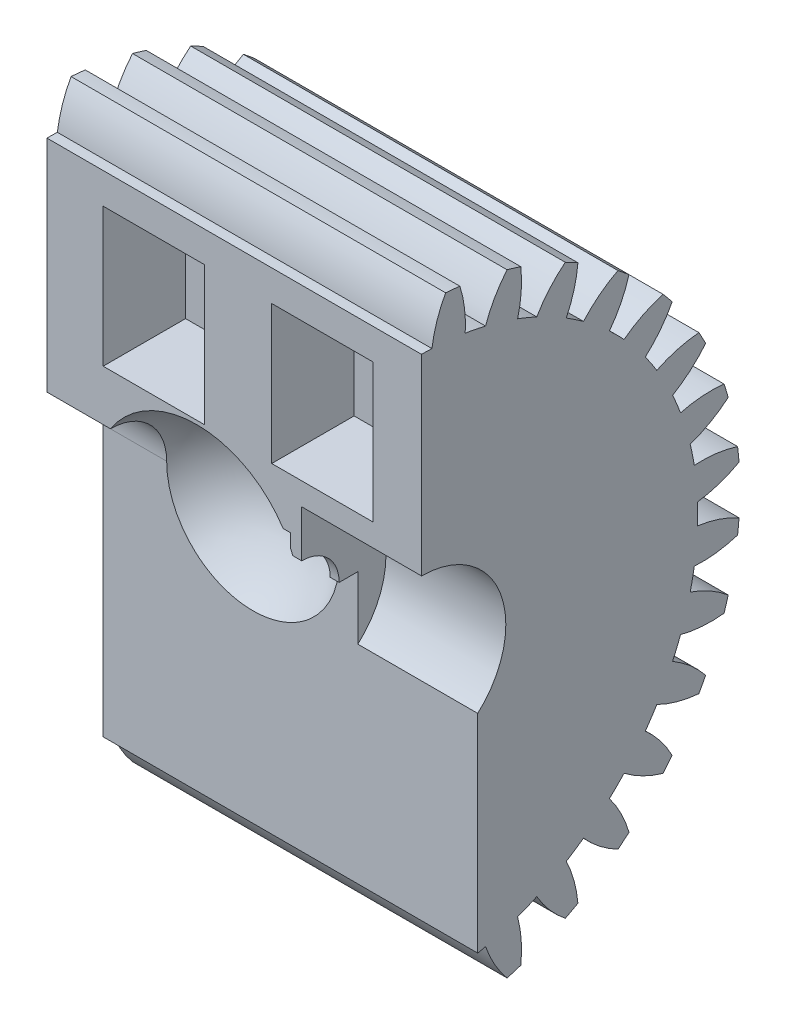
SolidWorks part; units mm, degrees
ref_plane "Plane1" through (0, 0, 0) normal (0, 0, 1) x (1, 0, 0)
ref_plane "Plane2" through (0, 0, 0) normal (0, 1, 0) x (1, 0, 0)
ref_plane "Plane3" through (0, 0, 0) normal (1, 0, 0) x (0, 0, -1)
other "Configuration Table"
sketch "HoldingSke" plane through (0, 0, 0) normal (0, 1, 0) x (1, 0, 0)
  line L0 (0, 0) -> (1.6961, -1.0598)
  line L1 (-15, 0) -> (100, 0) construction
  line L2 (0, 0) -> (-2.1039, 2.3779)
  line L3 (0, 0) -> (-11.863, 4.5341)
  line L4 (0, 0) -> (7.3237, 4.5764)
  line L5 (0, 0) -> (-46.8476, -17.4728)
  line L6 (0, 0) -> (-8.2896, -5.593)
  line L7 (-2.1039, 2.3779) -> (8.6586, 51.2059)
  line L8 (-76.2, 54.61) -> (-75.9, 54.61)
  line L9 (-67.7845, 28.3722) -> (-49.3413, 33.142)
  line L10 (-76.2, 71.12) -> (104.1128, 71.12)
  line L11 (0, 0) -> (-10, 0)
  line L12 (-76.2, 101.6) -> (-76.181, 101.6)
  line L13 (24.9733, 27.94) -> (52.9518, 28.4284)
  line L14 (24.9733, 27.94) -> (24.9743, 27.94)
  line L15 (24.9733, 27.94) -> (100.4006, 29.5858)
  line L16 (-63.627, -0.5) -> (-12.827, -0.5)
  circle A0 centre (0, 0) radius 1
  circle A1 centre (0, 0) radius 7.374
  circle A2 centre (0, 0) radius 37.5
  circle A3 centre (0, 0) radius 1
  dimension "MHD" = 14.748
  dimension "Hub_dia" = 75
  dimension "Bore" = 2
  dimension "MBD" = 2
  dimension "Num_teeth" = 32
  dimension "Pitch" = 2
  dimension "Overall_len" = 50
  dimension "Show_teeth" = 32
  dimension "Thickness" = 10
  dimension "OAL" = 50.0001
  dimension "T_dim" = 0.3
  dimension "Ap" = 14.5
  dimension "H" = 19.05
  dimension "Pitch_radius" = 180.3128
  dimension "Width" = 10
  dimension "Backlash" = 0.019
  dimension "Addendum_fac" = 1
  dimension "Dedendum_fac" = 1.25
  dimension "Clearance_fac" = 0.25
  dimension "Dedendum_add" = 0.001
  dimension "Module" = 0.5
sketch "BasProSke" plane through (0, 0, 0) normal (0, 1, 0) x (1, 0, 0)
  line L0 (-10, 0) -> (60, 0) construction
  line L1 (0, 0) -> (0, 8.5)
  line L2 (0, 0) -> (10, 0)
  line L3 (10, 0) -> (10, 8.5)
  line L4 (10, 8.5) -> (0, 8.5)
  dimension "Thickness" = 10
  dimension "Diameter" = 17
revolve "Base-Revolve" add sketch "BasProSke" angle 360 about L0
sketch "TooCutSke" plane through (0, 0, 0) normal (1, 0, 0) x (0, 0, -1)
  line L1 (0, 0) -> (0, 107) construction
  line L2 (0, 0) -> (-0.4258, 7.9887) construction
  line L3 (0, 0) -> (-1.5667, 15.9069) construction
  line L4 (-0.4258, 7.9887) -> (-0.7833, 7.9534) construction
  arc A0 (0.277, 7.3688) -> (-0.277, 7.3688) centre (0, 0) ccw
  arc A1 (0.6561, 8.5001) -> (-0.6561, 8.5001) centre (0, 0) ccw
  circle A2 centre (0, 0) radius 8 construction
  circle A3 centre (0, 0) radius 7.7452 construction
  arc A4 (-0.277, 7.3688) -> (-0.6561, 8.5001) centre (-3.4475, 6.9356) ccw
  arc A5 (0.6561, 8.5001) -> (0.277, 7.3688) centre (3.4475, 6.9356) ccw
  dimension "Root_dia" = 14.748
  dimension "Overcut_dia" = 17.0508
  dimension "Pitch_dia" = 16
  dimension "Base_dia" = 15.4904
  dimension "Flank_rad" = 3.2
  dimension "Half_ang" = 5.625
  dimension "Half_CT" = 0.3593
extrude "ToothCut" cut sketch "TooCutSke" along normal through all
fillet "Breaks" [suppressed] radius 0.01
fillet "RootFillets" [suppressed] radius 0.126
pattern_circular "TeethCuts" count 32 over 360 about axis through (0, 0, 0) along (1, 0, 0) of "ToothCut", "RootFillets", "Breaks"
sketch "HubNeaOneSke" plane through (0, 0, 0) normal (-1, 0, 0) x (0, 0, 1)
  circle A0 centre (0, 0) radius 7.374
  dimension "Diameter" = 14.748
extrude "HubNearOne" [suppressed] add sketch "HubNeaOneSke" along normal blind 40.0001
sketch "HubNeaBotSke" plane through (0, 0, 0) normal (-1, 0, 0) x (0, 0, 1)
  circle A0 centre (0, 0) radius 7.374
  dimension "Diameter" = 14.748
extrude "HubNearBoth" [suppressed] add sketch "HubNeaBotSke" along normal blind 20
ref_plane "FarPln" through (10, 0, 0) normal (1, 0, 0) x (0, 0, -1)
sketch "HubFarSke" plane through (10, 0, 0) normal (1, 0, 0) x (0, 0, -1)
  circle A0 centre (0, 0) radius 7.374
  dimension "Diameter" = 14.748
extrude "HubFar" [suppressed] add sketch "HubFarSke" along normal blind 20
sketch "BorSke" plane through (0, 0, 0) normal (1, 0, 0) x (0, 0, -1)
  circle A0 centre (0, 0) radius 1
  dimension "Diameter" = 2
extrude "Bore" cut sketch "BorSke" along normal mid plane 100.0001
sketch "KeySke" plane through (0, 0, 0) normal (1, 0, 0) x (0, 0, -1)
  line L0 (-0.4, 0) -> (-0.4, 1.3)
  line L1 (-0.4, 1.3) -> (0.4, 1.3)
  line L2 (0.4, 1.3) -> (0.4, 0)
  line L3 (0, 0) -> (0, 34) construction
  line L4 (-0.4, 0) -> (0.4, 0)
  dimension "Offset" = 1.3
  dimension "Width" = 0.8
extrude "Keyway" [suppressed] cut sketch "KeySke" along normal mid plane 100.0001
pattern_circular "Keyway2" [suppressed] count 2 every 90 about axis through (-10, 0, 0) along (1, 0, 0)
sketch "Sketch1" plane through (10, 0, 0) normal (1, 0, 0) x (0, 0, -1)
  circle A0 centre (0, 0) radius 2.25
  dimension "D1" = 4.5
extrude "Cut-Extrude1" cut sketch "Sketch1" against normal blind 3.2
sketch "Sketch2" plane through (0, 0, 0) normal (-1, 0, 0) x (0, 0, 1)
  line L1 (-1.5, 0) -> (1.5, 0)
  line L2 (-1.5, 0) -> (-1.5, -10)
  line L3 (-1.5, -10) -> (1.5, -10)
  line L4 (1.5, 0) -> (1.5, -10)
  circle A0 centre (0, 0) radius 1 construction
  dimension "D3" = 1.5
  dimension "D1" = 10
  dimension "D2" = 3
  dimension "D4" = 0
extrude "Cut-Extrude2" cut sketch "Sketch2" against normal through all
sketch "Sketch3" plane through (0, 0, -1.5) normal (0, 0, 1) x (1, 0, 0)
  line L0 (0, 0.277) -> (0, -0.277) construction
  circle A0 centre (4, 0) radius 0.6
  dimension "D1" = 4
extrude "Cut-Extrude3" cut sketch "Sketch3" against normal through all both and the other way through all
sketch "Sketch4" plane through (0, 0, 0) normal (-1, 0, 0) x (0, 0, 1)
  circle A0 centre (0, 0) radius 1.5
extrude "Cut-Extrude4" cut sketch "Sketch4" against normal blind 6.5
sketch "Sketch5" plane through (0, 0, 0) normal (0, 1, 0) x (1, 0, 0)
  line L0 (0, 0) -> (5, 0) construction
  line L1 (0, 0.277) -> (0, -0.277) construction
  line L3 (5, 8.4382) -> (5, -8.4382) construction
  line L4 (10, 8.4382) -> (0, 8.4382) construction
  line L5 (0, -8.4382) -> (10, -8.4382) construction
sketch "Sketch6" plane through (0, 0, 0) normal (0, 0, 1) x (1, 0, 0)
  line L0 (4, 0) -> (4, 2.75)
  line L1 (4, 0) -> (4, -2.75)
  arc A0 (4, 2.75) -> (4, -2.75) centre (4, 0) cw
  dimension "D1" = 2.75
  dimension "D2" = 2.75
revolve "Cut-Revolve1" cut sketch "Sketch6" angle 360 about L1
sketch "Sketch7" plane through (0, 0, 0) normal (0, 0, 1) x (1, 0, 0)
  line L1 (-0.5761, 8.9097) -> (10.3976, 8.9097)
  line L2 (-0.5761, 8.9097) -> (-0.5761, -8.6884)
  line L3 (-0.5761, -8.6884) -> (10.3976, -8.6884)
  line L4 (10.3976, 8.9097) -> (10.3976, -8.6884)
extrude "Cut-Extrude5" cut sketch "Sketch7" along normal blind 10
sketch "Sketch8" plane through (0, 0, 0) normal (0, 0, 1) x (1, 0, 0)
  line L0 (0, 7.374) -> (0, 1.5) construction
  line L1 (6, 6.55) -> (8.7, 6.55)
  line L2 (6, 6.55) -> (6, 2.85)
  line L3 (6, 2.85) -> (8.7, 2.85)
  line L4 (8.7, 6.55) -> (8.7, 2.85)
  line L5 (6, 6.55) -> (8.7, 2.85) construction
  line L6 (6, 2.85) -> (8.7, 6.55) construction
  line L7 (1.5, 6.55) -> (4.2, 6.55)
  line L8 (1.5, 6.55) -> (1.5, 2.85)
  line L9 (1.5, 2.85) -> (4.2, 2.85)
  line L10 (4.2, 6.55) -> (4.2, 2.85)
  line L11 (1.5, 6.55) -> (4.2, 2.85) construction
  line L12 (1.5, 2.85) -> (4.2, 6.55) construction
  point P0 (7.35, 4.7)
  point P5 (2.85, 4.7)
  dimension "D1" = 8.7
  dimension "D2" = 4.2
  dimension "D3" = 2.7
  dimension "D4" = 2.7
  dimension "D5" = 3.7
  dimension "D6" = 3.7
  dimension "D7" = 4.7
  dimension "D8" = 4.7
extrude "Cut-Extrude6" cut sketch "Sketch8" against normal blind 2.2
equation "' \"Module@HoldingSke\" = 6.35"
equation "' \"Num_teeth@HoldingSke\" = 12"
equation "' \"Ap@HoldingSke\" =  20"
equation "' \"Ap@HoldingSke\" = 20"
equation "' \"Width@HoldingSke\" = 0.5 * 25.4"
equation "' \"Hub_dia@HoldingSke\"= 1 * 25.4"
equation "' \"Hub_dia@HoldingSke\" = 1 * 25.4"
equation "' \"Overall_len@HoldingSke\" = 1.0 * 25.4"
equation "' \"Bore@HoldingSke\" = 0.75 * 25.4"
equation "' \"T_dim@HoldingSke\" = 0.1 * 25.4"
equation "' \"Width@KeySke\" = 0.25 * 25.4"
equation "' \"Show_teeth@HoldingSke\" = 13"
equation "' \"Backlash@HoldingSke\" = 0.009 * 25.4"
equation "' \"Addendum_fac@HoldingSke\" = 1.0"
equation "' \"Dedendum_fac@HoldingSke\" = 1.25"
equation "' \"Dedendum_add@HoldingSke\" = 0.00005 * 25.4"
equation "' \"Clearance_fac@HoldingSke\" = 0.25"
equation "\"Pitch@HoldingSke\" = 1 / \"Module@HoldingSke\""
equation "\"Overcut_dia@TooCutSke\" = (\"Num_teeth@HoldingSke\" + 2 * \"Addendum_fac@HoldingSke\") / \"Pitch@HoldingSke\" + 0.002 * 25.4"
equation "\"Pitch_dia@TooCutSke\" = \"Num_teeth@HoldingSke\" / \"Pitch@HoldingSke\""
equation "\"Base_dia@TooCutSke\" = \"Num_teeth@HoldingSke\" / \"Pitch@HoldingSke\" * cos((\"Ap@HoldingSke\"  * 3.14159265 / 180))"
equation "\"Root_dia@TooCutSke\" = (\"Num_teeth@HoldingSke\" + 2) / \"Pitch@HoldingSke\" - 2 * (\"Addendum_fac@HoldingSke\" + \"Dedendum_fac@HoldingSke\") / \"Pitch@HoldingSke\" - \"Dedendum_add@HoldingSke\" * 2"
equation "\"Half_ang@TooCutSke\" = 180 / \"Num_teeth@HoldingSke\""
equation "\"Half_CT@TooCutSke\" = \"Num_teeth@HoldingSke\" / \"Pitch@HoldingSke\" * sin((3.14159265 / 2 / \"Num_teeth@HoldingSke\")) / 2 - 7 * \"Backlash@HoldingSke\" / 4"
equation "\"Flank_rad@TooCutSke\" = \"Num_teeth@HoldingSke\" / \"Pitch@HoldingSke\" / 5"
equation "\"Radius@RootFillets\" = \"Clearance_fac@HoldingSke\" / \"Pitch@HoldingSke\" + \"Dedendum_add@HoldingSke\""
equation "\"Break_rad@Breaks\" = 0.02 / \"Pitch@HoldingSke\""
equation "\"Thickness@HoldingSke\" = \"Width@HoldingSke\""
equation "\"OAL@HoldingSke\" = \"Thickness@HoldingSke\""
equation "\"MHD@HoldingSke\" = (\"Num_teeth@HoldingSke\" + 2) / \"Pitch@HoldingSke\" - 2 * (\"Addendum_fac@HoldingSke\" + \"Dedendum_fac@HoldingSke\")  / \"Pitch@HoldingSke\" - \"Dedendum_add@HoldingSke\" * 2"
equation "\"MBD@HoldingSke\" = (\"Num_teeth@HoldingSke\" + 2) / \"Pitch@HoldingSke\" - 2 * (\"Addendum_fac@HoldingSke\" + \"Dedendum_fac@HoldingSke\")  / \"Pitch@HoldingSke\" - \"Dedendum_add@HoldingSke\" * 2 - 0.002 * 25.4"
equation "\"MHD@HoldingSke\" = ((sgn( \"MHD@HoldingSke\" - \"Hub_dia@HoldingSke\" )-1)*( \"MHD@HoldingSke\" - \"Hub_dia@HoldingSke\" ))/-2+ \"Hub_dia@HoldingSke\""
equation "\"MBD@HoldingSke\" = ((sgn( \"MBD@HoldingSke\" - \"Bore@HoldingSke\" )-1)*( \"MBD@HoldingSke\" - \"Bore@HoldingSke\" ))/-2+ \"Bore@HoldingSke\""
equation "\"OAL@HoldingSke\" = ((sgn( \"OAL@HoldingSke\" - \"Overall_len@HoldingSke\" )+1)*( \"OAL@HoldingSke\" - \"Overall_len@HoldingSke\" ))/2 + \"Overall_len@HoldingSke\" + 0.000002 * 25.4"
equation "\"Num_teeth@TeethCuts\" = int( \"Show_teeth@HoldingSke\" ) + 1"
equation "\"Num_teeth@TeethCuts\" = ((sgn( \"Num_teeth@TeethCuts\" - \"Num_teeth@HoldingSke\" )-1)*( \"Num_teeth@TeethCuts\" - \"Num_teeth@HoldingSke\" ))/-2+ \"Num_teeth@HoldingSke\""
equation "\"Num_teeth@TeethCuts\" = ((sgn( \"Num_teeth@TeethCuts\" - 2.0)+1)*( \"Num_teeth@TeethCuts\" - 2.0))/2 +2.0"
equation "\"Angle@TeethCuts\" = 360.0 / \"Num_teeth@HoldingSke\""
equation "\"Diameter@BasProSke\" = (\"Num_teeth@HoldingSke\" + 2 * \"Addendum_fac@HoldingSke\") / \"Pitch@HoldingSke\""
equation "\"Thickness@BasProSke\"  = \"Thickness@HoldingSke\""
equation "' \"Fillet_rad@BasProSke\" =  \"Thickness@HoldingSke\" * 0.05"
equation "' \"Fillet_rad@BasProSke\" = \"Thickness@HoldingSke\" * 0.05"
equation "\"MHD@HoldingSke\" = ((sgn( \"MHD@HoldingSke\" - \"Root_dia@TooCutSke\" )-1)*( \"MHD@HoldingSke\" - \"Root_dia@TooCutSke\" ))/-2+ \"Root_dia@TooCutSke\""
equation "\"Diameter@HubNeaOneSke\" = \"MHD@HoldingSke\""
equation "\"Length@HubNearOne\" = \"OAL@HoldingSke\" - \"Thickness@BasProSke\""
equation "\"Diameter@HubNeaBotSke\" = \"MHD@HoldingSke\""
equation "\"Length@HubNearBoth\" = ( \"OAL@HoldingSke\" - \"Thickness@BasProSke\" ) / 2.0"
equation "\"Thickness@FarPln\" = \"Thickness@BasProSke\""
equation "\"Diameter@HubFarSke\" = \"MHD@HoldingSke\""
equation "\"Length@HubFar\" = ( \"OAL@HoldingSke\" - \"Thickness@BasProSke\" ) / 2.0"
equation "\"Diameter@BorSke\" = \"MBD@HoldingSke\""
equation "\"D1@Bore\" = \"OAL@HoldingSke\" * 2.0"
equation "\"D1@Keyway\" = \"OAL@HoldingSke\" * 2.0"
equation "\"Offset@KeySke\" = \"T_dim@HoldingSke\" + \"MBD@HoldingSke\" / 2.0"
